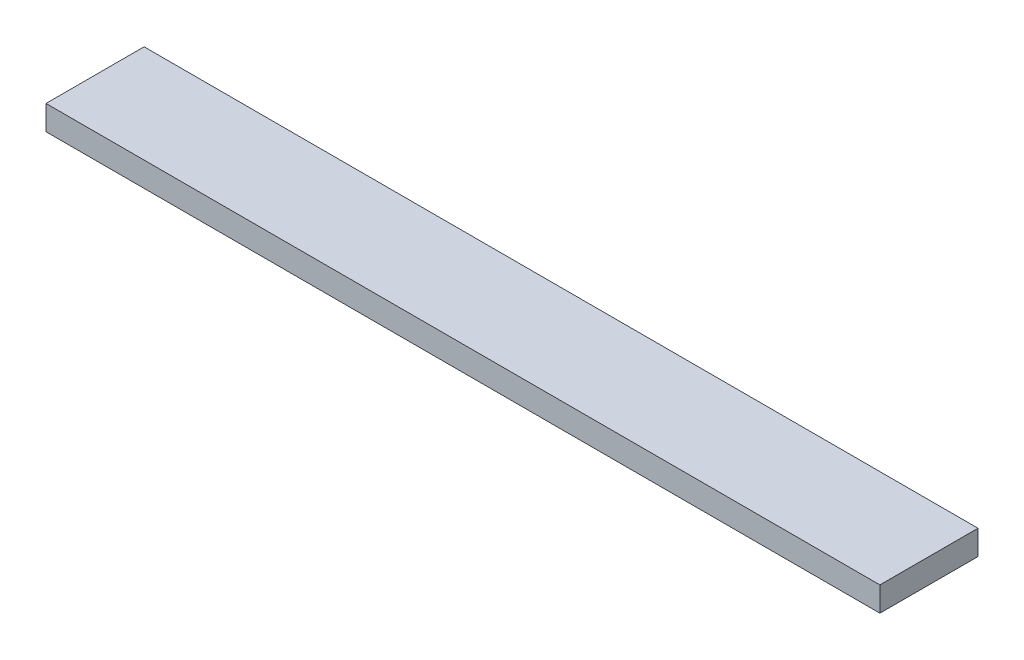
SolidWorks part; units mm, degrees
ref_plane "Front Plane" through (0, 0, 0) normal (0, 0, 1) x (1, 0, 0)
ref_plane "Top Plane" through (0, 0, 0) normal (0, 1, 0) x (1, 0, 0)
ref_plane "Right Plane" through (0, 0, 0) normal (1, 0, 0) x (0, 0, -1)
sketch "Sketch1" plane through (0, 0, 0) normal (0, 0, 1) x (1, 0, 0)
  line L1 (-85, -2.5) -> (85, -2.5)
  line L2 (-85, -2.5) -> (-85, 2.5)
  line L3 (-85, 2.5) -> (85, 2.5)
  line L4 (85, -2.5) -> (85, 2.5)
  line L5 (-85, -2.5) -> (85, 2.5) construction
  line L6 (-85, 2.5) -> (85, -2.5) construction
  point P1 (0, 0)
  dimension "D1" = 170
  dimension "D2" = 5
extrude "Boss-Extrude1" add sketch "Sketch1" along normal blind 20
